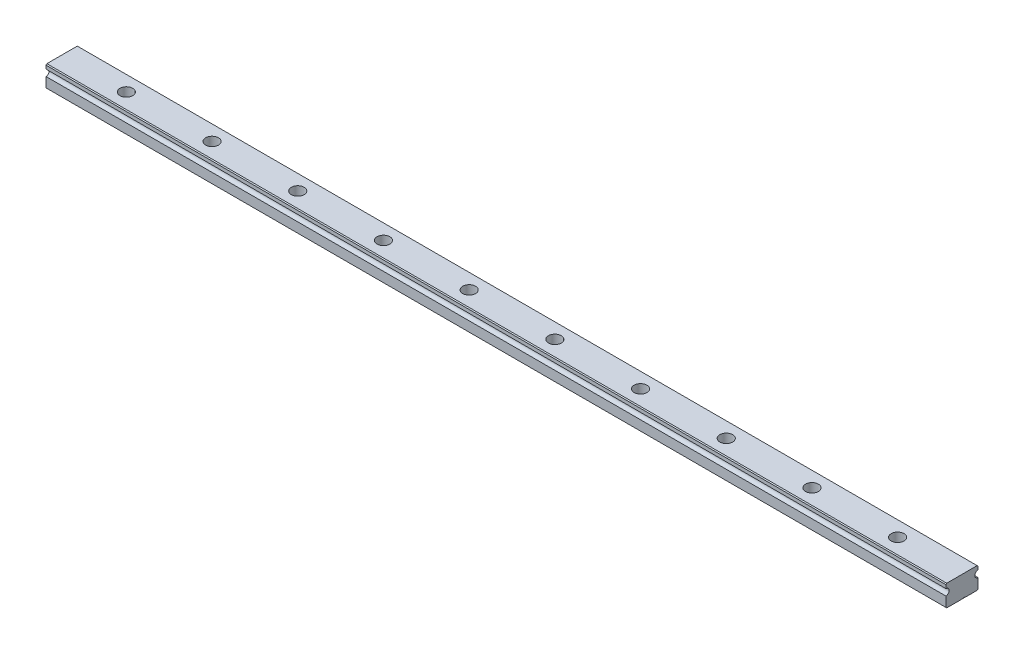
SolidWorks part; units mm, degrees
ref_plane "前视基准面" through (0, 0, 0) normal (0, 0, 1) x (1, 0, 0)
ref_plane "上视基准面" through (0, 0, 0) normal (0, 1, 0) x (1, 0, 0)
ref_plane "右视基准面" through (0, 0, 0) normal (1, 0, 0) x (0, 0, -1)
sketch "草图1" plane through (0, 0, 0) normal (1, 0, 0) x (0, 0, -1)
  line L22 (-7.5, 5) -> (-7.5, 0.4)
  line L23 (-7.5, 0.4) -> (-7.1, 0)
  line L24 (-7.1, 0) -> (0.7, 0)
  line L25 (1.3, 0) -> (7.1, 0)
  line L26 (7.1, 0) -> (7.5, 0.4)
  line L27 (7.5, 0.4) -> (7.5, 5)
  line L28 (7.5, 8) -> (7.5, 9.6)
  line L29 (7.5, 9.6) -> (7.1, 10)
  line L30 (7.1, 10) -> (-7.1, 10)
  line L31 (-7.1, 10) -> (-7.5, 9.6)
  line L32 (-7.5, 9.6) -> (-7.5, 8)
  arc A10 (-7.5, 5) -> (-6, 6.5) centre (-7.5, 6.5) ccw
  arc A11 (1.3, 0) -> (0.7, 0) centre (1, 0) ccw
  arc A12 (6, 6.5) -> (7.5, 5) centre (7.5, 6.5) ccw
  arc A13 (7.5, 8) -> (6, 6.5) centre (7.5, 6.5) ccw
  arc A14 (-6, 6.5) -> (-7.5, 8) centre (-7.5, 6.5) ccw
extrude "凸台-拉伸1" add sketch "草图1" along normal mid plane 420
sketch "草图2" plane through (0, 10, 0) normal (0, 1, 0) x (1, 0, 0)
  line L0 (-210, 7.1) -> (-210, -7.1) construction
  circle A0 centre (-180, 0) radius 3
  point P5 (-210, 0)
  dimension "D1" = 6
  dimension "D2" = 30
extrude "切除-拉伸1" cut sketch "草图2" against normal blind 4.5
sketch "草图4" plane through (0, 5.5, 0) normal (0, 1, 0) x (1, 0, 0)
  circle A0 centre (-180, 0) radius 1.75
  dimension "D1" = 3.5
extrude "切除-拉伸2" cut sketch "草图4" against normal through all
pattern_linear "阵列(线性)1" count 15 spacing 40 along (1, 0, 0) of "切除-拉伸2", "切除-拉伸1"
